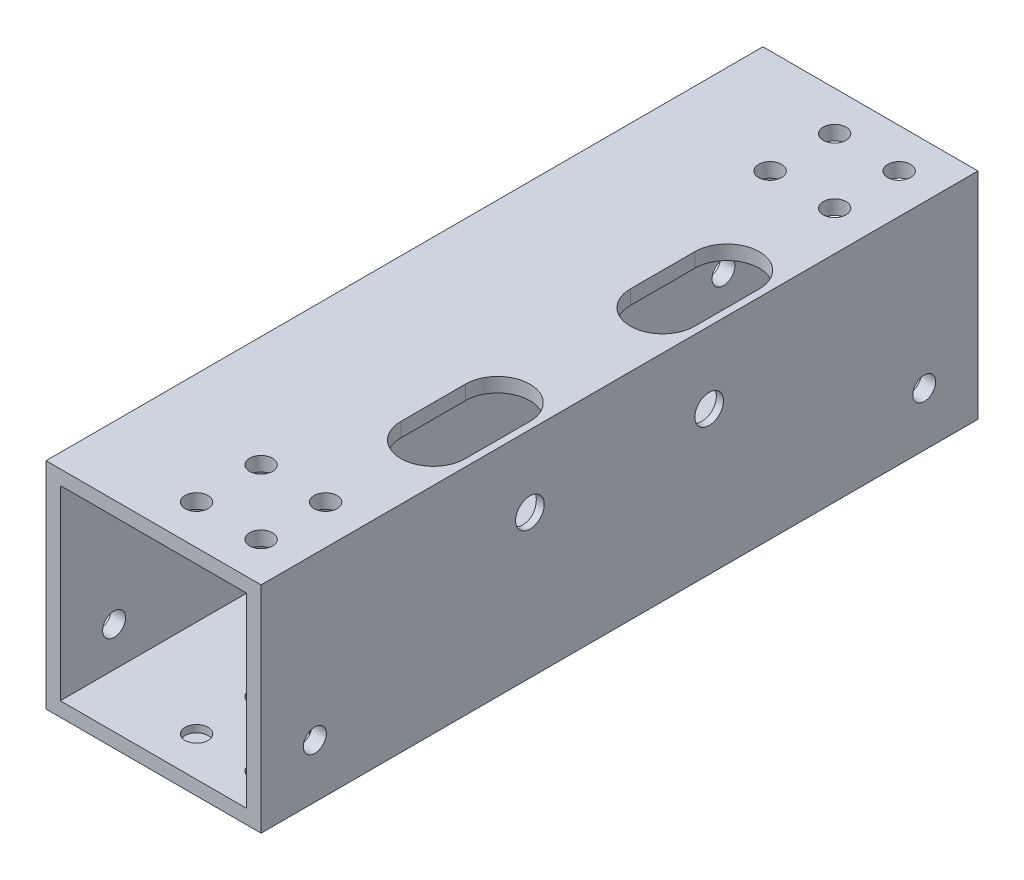
SolidWorks part; units mm, degrees
material "6061-T6 (SS)"
ref_plane "前视基准面" through (0, 0, 0) normal (0, 0, 1) x (1, 0, 0)
ref_plane "上视基准面" through (0, 0, 0) normal (0, 1, 0) x (1, 0, 0)
ref_plane "右视基准面" through (0, 0, 0) normal (1, 0, 0) x (0, 0, -1)
sketch "草图1" plane through (0, 0, 0) normal (0, 0, 1) x (1, 0, 0)
  line L1 (-15, 15) -> (15, 15)
  line L2 (-15, 15) -> (-15, -15)
  line L3 (-15, -15) -> (15, -15)
  line L4 (15, 15) -> (15, -15)
  line L5 (-15, 15) -> (15, -15) construction
  line L6 (-15, -15) -> (15, 15) construction
  line L7 (-13, 13) -> (13, 13)
  line L8 (-13, 13) -> (-13, -13)
  line L9 (-13, -13) -> (13, -13)
  line L10 (13, 13) -> (13, -13)
  line L11 (-13, 13) -> (13, -13) construction
  line L12 (-13, -13) -> (13, 13) construction
  point P0 (0, 0)
  point P6 (0, 0)
  dimension "D1" = 30
  dimension "D2" = 30
  dimension "D3" = 26
  dimension "D4" = 26
extrude "凸台-拉伸1" add sketch "草图1" along normal blind 100
sketch "草图3" plane through (0, 15, 0) normal (0, 1, 0) x (1, 0, 0)
  line L1 (15, -100) -> (-5, -100) construction
  line L2 (15, -100) -> (15, -80) construction
  line L3 (15, -80) -> (-5, -80) construction
  line L4 (-5, -100) -> (-5, -80) construction
  line L5 (15, -100) -> (-5, -80) construction
  line L6 (15, -80) -> (-5, -100) construction
  line L7 (0.5, -85.5) -> (9.5, -85.5) construction
  line L8 (0.5, -85.5) -> (0.5, -94.5) construction
  line L9 (0.5, -94.5) -> (9.5, -94.5) construction
  line L10 (9.5, -85.5) -> (9.5, -94.5) construction
  line L11 (0.5, -85.5) -> (9.5, -94.5) construction
  line L12 (0.5, -94.5) -> (9.5, -85.5) construction
  line L13 (-15, 0) -> (15, 0) construction
  line L14 (-15, 0) -> (-15, -100) construction
  line L15 (-15, -100) -> (15, -100) construction
  line L16 (15, 0) -> (15, -100) construction
  line L17 (0, -100) -> (0, 0) construction
  line L18 (-15, -50) -> (15, -50) construction
  circle A0 centre (0.5, -94.5) radius 1.6
  circle A1 centre (9.5, -94.5) radius 1.6
  circle A2 centre (9.5, -85.5) radius 1.6
  circle A3 centre (0.5, -85.5) radius 1.6
  circle A4 centre (9.5, -14.5) radius 1.6
  circle A5 centre (9.5, -5.5) radius 1.6
  circle A6 centre (0.5, -5.5) radius 1.6
  circle A7 centre (0.5, -14.5) radius 1.6
  circle A8 centre (9.5, -70.5) radius 1.6
  circle A9 centre (9.5, -61.5) radius 1.6
  circle A10 centre (9.5, -38.5) radius 1.6
  circle A11 centre (9.5, -29.5) radius 1.6
  point P4 (5, -90)
  point P6 (5, -90)
  point P258 (0, -50)
  dimension "D4" = 2
  dimension "D1" = 20
  dimension "D2" = 20
  dimension "D3" = 9
  dimension "D5" = 2
  dimension "D6" = 2
extrude "切除-拉伸1" cut sketch "草图3" against normal through all
sketch "草图5" plane through (15, 0, 0) normal (1, 0, 0) x (0, 0, -1)
  line L0 (-100, -15) -> (0, -15) construction
  line L1 (-100, 15) -> (-85, 15) construction
  line L2 (-100, 15) -> (-100, -15) construction
  line L3 (-100, -15) -> (-85, -15) construction
  line L4 (-85, 15) -> (-85, -15) construction
  line L5 (-92.5, -15) -> (-92.5, 15) construction
  line L6 (-100, 0) -> (-85, 0) construction
  line L8 (-100, -15) -> (-85, -15) construction
  line L9 (-100, -15) -> (-100, 0) construction
  line L10 (-100, 0) -> (-85, 0) construction
  line L11 (-85, -15) -> (-85, 0) construction
  line L12 (-92.5, 0) -> (-92.5, -15) construction
  line L13 (-100, -7.5) -> (-85, -7.5) construction
  circle A0 centre (-92.5, -7.5) radius 1.6
  circle A1 centre (-7.5, -7.5) radius 1.6
  point P160 (-92.5, -7.5)
  point P196 (-92.5, 0)
  dimension "D3" = 2
  dimension "D1" = 15
  dimension "D2" = 15
extrude "切除-拉伸3" cut sketch "草图5" against normal through all
sketch "草图6" plane through (15, 0, 0) normal (1, 0, 0) x (0, 0, -1)
  line L1 (-100, 15) -> (0, 15) construction
  line L2 (-100, 15) -> (-100, -15) construction
  line L3 (-100, -15) -> (0, -15) construction
  line L4 (0, 15) -> (0, -15) construction
  line L5 (-50, -15) -> (-50, 15) construction
  line L6 (-100, 0) -> (0, 0) construction
  line L7 (-62.5, 5) -> (-37.5, 5) construction
  line L8 (-62.5, 5) -> (-62.5, -5) construction
  line L9 (-62.5, -5) -> (-37.5, -5) construction
  line L10 (-37.5, 5) -> (-37.5, -5) construction
  line L11 (-62.5, 5) -> (-37.5, -5) construction
  line L12 (-62.5, -5) -> (-37.5, 5) construction
  circle A0 centre (-62.5, 5) radius 2
  circle A1 centre (-37.5, 5) radius 2
  point P4 (-50, 0)
  point P364 (-50, 0)
  dimension "D1" = 25
  dimension "D2" = 10
extrude "切除-拉伸4" cut sketch "草图6" against normal through all
sketch "草图7" plane through (0, -15, 0) normal (0, -1, 0) x (1, 0, 0)
  line L1 (-4.5216, 98.5429) -> (13.0528, 98.5429)
  line L2 (-4.5216, 98.5429) -> (-4.5216, 80.7125)
  line L3 (-4.5216, 80.7125) -> (13.0528, 80.7125)
  line L4 (13.0528, 98.5429) -> (13.0528, 80.7125)
  line L5 (4.2656, 80.7125) -> (4.2656, 98.5429) construction
  line L6 (-4.5216, 89.6277) -> (13.0528, 89.6277) construction
  line L7 (-3.7538, 20.0553) -> (13.0528, 20.0553)
  line L8 (-3.7538, 20.0553) -> (-3.7538, 1.2012)
  line L9 (-3.7538, 1.2012) -> (13.0528, 1.2012)
  line L10 (13.0528, 20.0553) -> (13.0528, 1.2012)
  line L11 (4.6495, 1.2012) -> (4.6495, 20.0553) construction
  line L12 (-3.7538, 10.6282) -> (13.0528, 10.6282) construction
  point P68 (4.6495, 10.6282)
  point P76 (4.2656, 89.6277)
extrude "凸台-拉伸2" add sketch "草图7" against normal blind 1
sketch "草图8" plane through (0, -15, 0) normal (0, -1, 0) x (1, 0, 0)
  line L0 (9.5, 70.5) -> (9.5, 61.5) construction
  line L1 (14, 70.5) -> (14, 61.5)
  line L2 (5, 70.5) -> (5, 61.5)
  line L3 (15, 100) -> (15, 0) construction
  line L4 (9.5, 29.5) -> (9.5, 38.5) construction
  line L5 (-15, 0) -> (15, 0) construction
  line L6 (-15, 0) -> (-15, 100) construction
  line L7 (-15, 100) -> (15, 100) construction
  line L8 (15, 0) -> (15, 100) construction
  line L9 (0, 100) -> (0, 0) construction
  line L10 (-15, 50) -> (15, 50) construction
  line L11 (14, 29.5) -> (14, 38.5)
  line L12 (5, 29.5) -> (5, 38.5)
  circle A0 centre (9.5, 70.5) radius 1.6 construction
  arc A1 (14, 70.5) -> (5, 70.5) centre (9.5, 70.5) ccw
  circle A2 centre (9.5, 61.5) radius 1.6 construction
  arc A3 (5, 61.5) -> (14, 61.5) centre (9.5, 61.5) ccw
  arc A4 (14, 29.5) -> (5, 29.5) centre (9.5, 29.5) cw
  arc A5 (5, 38.5) -> (14, 38.5) centre (9.5, 38.5) cw
  point P0 (9.5, 66)
  point P17 (9.5, 34)
  point P179 (0, 50)
  dimension "D1" = 5.5
  dimension "D2" = 9
  dimension "D3" = 9
extrude "切除-拉伸5" cut sketch "草图8" against normal up to next
